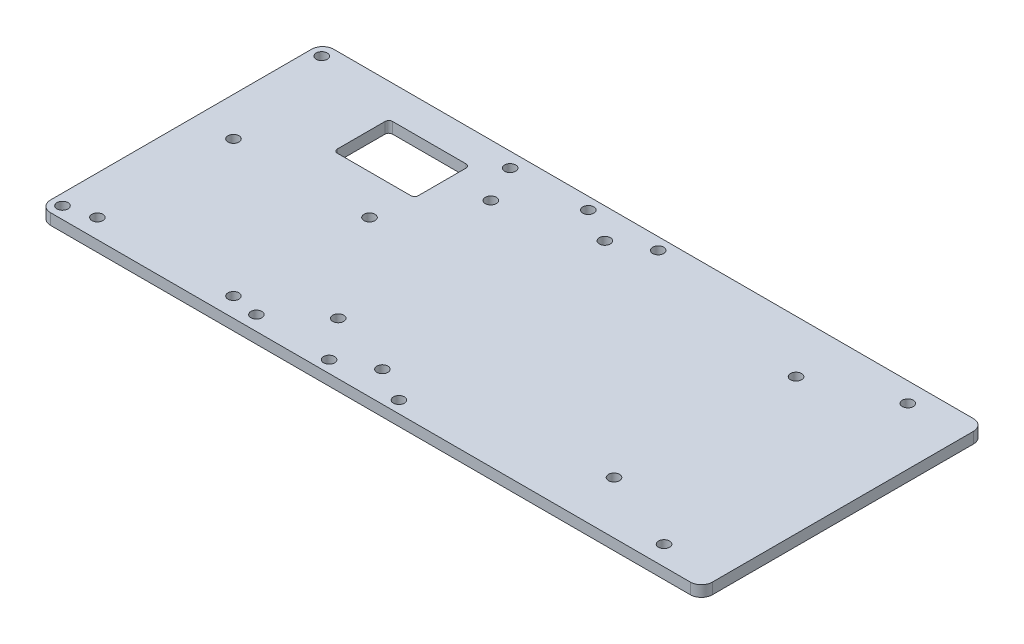
SolidWorks part; units mm, degrees
ref_plane "Front Plane" through (0, 0, 0) normal (0, 0, 1) x (1, 0, 0)
ref_plane "Top Plane" through (0, 0, 0) normal (0, 1, 0) x (1, 0, 0)
ref_plane "Right Plane" through (0, 0, 0) normal (1, 0, 0) x (0, 0, -1)
sketch "Sketch1" plane through (0, 0, 0) normal (0, 1, 0) x (1, 0, 0)
  line L0 (-90, 0) -> (0, 0) construction
  line L1 (-90, -38.5) -> (90, -38.5)
  line L2 (-90, -38.5) -> (-90, 38.5)
  line L3 (-90, 38.5) -> (90, 38.5)
  line L4 (90, -38.5) -> (90, 38.5)
  line L5 (-90, -38.5) -> (90, 38.5) construction
  line L6 (-90, 38.5) -> (90, -38.5) construction
  line L7 (-87, 35.25) -> (-34.7739, 35.25) construction
  line L8 (74.4946, 33.15) -> (74.4946, -33.15) construction
  line L9 (-87, 35.25) -> (-87, -35.25) construction
  circle A0 centre (-87, 35.25) radius 1.5
  circle A2 centre (-87, -35.25) radius 1.5
  circle A3 centre (-35.0054, 34.5) radius 1.5
  circle A4 centre (-35.0054, -34.5) radius 1.5
  circle A6 centre (74.4946, 33.15) radius 1.5007
  circle A7 centre (74.4946, -33.15) radius 1.5
  point P0 (0, 0)
  point P21 (74.4946, 0)
  dimension "D3" = 70.5
  dimension "D5" = 3
  dimension "D7" = 3
  dimension "D10" = 3.0015
  dimension "D14" = 3
  dimension "D1" = 180
  dimension "D2" = 66.3
  dimension "D4" = 77
  dimension "D6" = 52
  dimension "D8" = 109.5
  dimension "D9" = 3
extrude "Boss-Extrude1" add sketch "Sketch1" along normal blind 3
fillet "Fillet1" radius 3 4 edges at (-90, 1.5, -38.5) (-90, 1.5, 38.5) (90, 1.5, 38.5) (90, 1.5, -38.5)
sketch "Sketch2" plane through (0, 3, 0) normal (0, 1, 0) x (1, 0, 0)
  line L0 (87, 38.5) -> (-87, 38.5) construction
  line L1 (-62, 14.5) -> (-42, 14.5)
  line L2 (-63, 15.5) -> (-63, 28.5)
  line L3 (-62, 29.5) -> (-42, 29.5)
  line L4 (-41, 15.5) -> (-41, 28.5)
  line L5 (-63, 14.5) -> (-41, 29.5) construction
  line L6 (-63, 29.5) -> (-41, 14.5) construction
  line L7 (-90, 35.5) -> (-90, -35.5) construction
  arc A0 (-42, 29.5) -> (-41, 28.5) centre (-42, 28.5) cw
  arc A1 (-42, 14.5) -> (-41, 15.5) centre (-42, 15.5) ccw
  arc A2 (-62, 14.5) -> (-63, 15.5) centre (-62, 15.5) cw
  arc A3 (-62, 29.5) -> (-63, 28.5) centre (-62, 28.5) ccw
  point P0 (-52, 22)
  dimension "D5" = 1
  dimension "D1" = 22
  dimension "D2" = 15
  dimension "D3" = 9
  dimension "D4" = 27
extrude "Cut-Extrude1" cut sketch "Sketch2" against normal up to surface (3 mm away) up to face at (74.4946, 0, -31.6493)
sketch "Sketch3" plane through (0, 3, 0) normal (0, 1, 0) x (1, 0, 0)
  circle A0 centre (-79.5, 3.75) radius 1.5
  circle A1 centre (-42.5, 3.75) radius 1.5
  circle A2 centre (-42.5, -33.25) radius 1.5
  circle A3 centre (-79.5, -33.25) radius 1.5
  circle A4 centre (-87, -35.25) radius 1.5 construction
  dimension "D1" = 3
  dimension "D5" = 7.5
  dimension "D2" = 37
  dimension "D3" = 37
  dimension "D4" = 2
extrude "Cut-Extrude2" cut sketch "Sketch3" against normal up to surface (3 mm away) up to face at (-52, 0, -22)
sketch "Sketch4" plane through (0, 3, 0) normal (0, 1, 0) x (1, 0, 0)
  line L0 (87, 38.5) -> (-87, 38.5) construction
  circle A0 centre (-30.0054, 24.25) radius 1.5
  circle A1 centre (52.9946, 24.25) radius 1.5
  circle A2 centre (51.9946, -24.25) radius 1.5
  circle A3 centre (-23.0054, -24.25) radius 1.5
  circle A4 centre (-35.0054, 34.5) radius 1.5 construction
  dimension "D1" = 3
  dimension "D4" = 83
  dimension "D5" = 1
  dimension "D7" = 5
  dimension "D2" = 48.5
  dimension "D3" = 75
  dimension "D6" = 14.25
extrude "Cut-Extrude3" cut sketch "Sketch4" against normal up to surface (3 mm away) up to face at (-79.5, 0, 31.75)
sketch "Sketch5" plane through (0, 0, 0) normal (0, -1, 0) x (1, 0, 0)
  line L0 (87, -38.5) -> (-87, -38.5) construction
  line L1 (30, -15.5) -> (50, -15.5)
  line L2 (30, -15.5) -> (30, 18.5)
  line L3 (30, 18.5) -> (50, 18.5)
  line L4 (50, -15.5) -> (50, 18.5)
  line L5 (30, -15.5) -> (50, 18.5) construction
  line L6 (30, 18.5) -> (50, -15.5) construction
  line L7 (90, 35.5) -> (90, -35.5) construction
  point P0 (40, 1.5)
  dimension "D1" = 34
  dimension "D2" = 23
  dimension "D3" = 20
  dimension "D4" = 40
extrude "Boss-Extrude2" add sketch "Sketch5" along normal blind 20
sketch "Sketch6" plane through (0, 0, 0) normal (0, -1, 0) x (1, 0, 0)
  line L0 (87, -38.5) -> (-87, -38.5) construction
  line L1 (-14.5, -35.25) -> (4.5, -35.25) construction
  line L2 (-90, -35.5) -> (-90, 35.5) construction
  line L3 (-90, 0) -> (-108.2939, 0) construction
  line L4 (-14.5, 35.25) -> (4.5, 35.25) construction
  circle A0 centre (-14.5, -35.25) radius 1.5
  circle A1 centre (4.5, -35.25) radius 1.5
  circle A2 centre (4.5, 35.25) radius 1.5
  circle A3 centre (-14.5, 35.25) radius 1.5
  circle A4 centre (-5, -30.25) radius 1.5
  circle A5 centre (-5, 30.25) radius 1.5
  point P4 (-5, -35.25)
  dimension "D1" = 3
  dimension "D3" = 3.25
  dimension "D6" = 9.5
  dimension "D2" = 19
  dimension "D4" = 85
  dimension "D5" = 5
extrude "Cut-Extrude4" cut sketch "Sketch6" against normal up to surface (3 mm away) up to face at (-30.0054, 3, -22.75)
